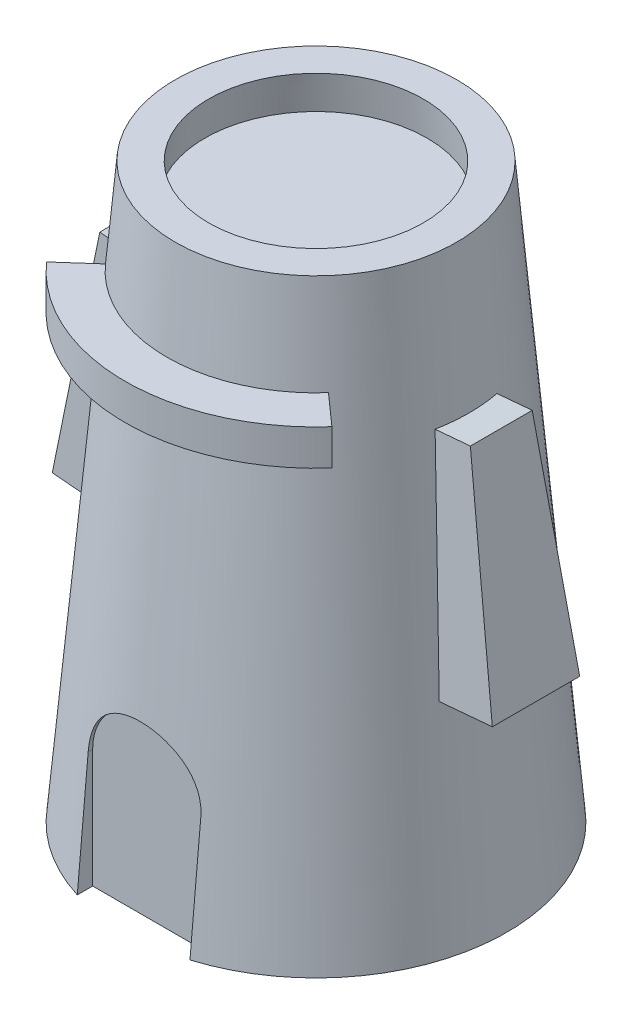
SolidWorks part; units mm, degrees
ref_plane "前视基准面" through (0, 0, 0) normal (0, 0, 1) x (1, 0, 0)
ref_plane "上视基准面" through (0, 0, 0) normal (0, 1, 0) x (1, 0, 0)
ref_plane "右视基准面" through (0, 0, 0) normal (1, 0, 0) x (0, 0, -1)
other "Configuration Table"
sketch "草图1" plane through (0, 0, 0) normal (0, 1, 0) x (1, 0, 0)
  circle A0 centre (0, 0) radius 16
extrude "凸台-拉伸1" add sketch "草图1" along normal blind 48 draft 5
sketch "草图2" plane through (0, 48, 0) normal (0, 1, 0) x (1, 0, 0)
  circle A0 centre (0, 0) radius 9
extrude "切除-拉伸1" cut sketch "草图2" against normal blind 3 draft 6 draft outward yes
ref_plane "基准面1" through (0, 0, 16) normal (0, 0, 1) x (1, 0, 0)
sketch "草图3" plane through (0, 0, 16) normal (0, 0, 1) x (1, 0, 0)
  line L0 (-4.7214, 0) -> (4.7214, 0)
  line L2 (4.7214, 0) -> (4.7214, 9.9321)
  line L4 (-4.7214, 0) -> (-4.7214, 9.9321)
  arc A0 (4.7214, 9.9321) -> (-4.7214, 9.9321) centre (0, 9.9321) ccw
  point P0 (0, 0)
extrude "切除-拉伸2" cut sketch "草图3" against normal blind 2
ref_plane "基准面2" through (0, 0, 14) normal (0, 0, 1) x (1, 0, 0)
sketch "草图5" plane through (0, 0, 14) normal (0, 0, 1) x (1, 0, 0)
  line L0 (-16.397, 0) -> (16.397, 0)
  line L1 (-16.397, 9.9321) -> (16.397, 9.9321)
  line L3 (16.397, 0) -> (16.397, 9.9321)
  line L4 (0, -55) -> (0, 55) construction
  line L5 (-16.397, 0) -> (-16.397, 9.9321)
  line L6 (4.7214, 0) -> (4.7214, 9.9321) construction
  line L7 (-4.7214, 0) -> (-4.7214, 9.9321) construction
  line L8 (4.7214, 0) -> (4.7214, 9.9321)
  line L9 (-4.7214, 0) -> (-4.7214, 9.9321)
  line L10 (4.7214, 9.9321) -> (4.7214, 0) construction
  line L11 (4.7214, 9.9321) -> (4.7214, 0)
  line L12 (-4.7214, 0) -> (-4.7214, 9.9321)
sketch "草图6" plane through (0, 0, 0) normal (0, 1, 0) x (1, 0, 0)
  circle A0 centre (0, 0) radius 12.5
  point P0 (0, 0)
ref_plane "基准面3" through (0, 40, 0) normal (0, 1, 0) x (1, 0, 0)
extrude "切除-拉伸3" cut sketch "草图6" along normal blind 43 draft 5
sketch "草图8" plane through (0, 40, 0) normal (0, 1, 0) x (1, 0, 0)
  line L1 (0, 0) -> (0, -23.7426) construction
  line L4 (-11.9615, -10.6266) -> (-9.3452, -8.3023)
  line L5 (11.9615, -10.6266) -> (9.3452, -8.3023)
  circle A0 centre (0, 0) radius 12.5005
  arc A1 (-9.3452, -8.3023) -> (9.3452, -8.3023) centre (0, 0) ccw
  arc A2 (-11.9615, -10.6266) -> (11.9615, -10.6266) centre (0, 0) ccw
  arc A3 (4.7214, -15.2875) -> (-4.7214, -15.2875) centre (0, 0) ccw construction
extrude "凸台-拉伸2" add sketch "草图8" against normal blind 3
ref_plane "基准面4" through (15.8785, 1.3892, 0) normal (0.9962, 0.0872, 0) x (0, 0, -1)
sketch "草图9" plane through (15.8785, 1.3892, 0) normal (0.9962, 0.0872, 0) x (0, 0, -1)
  line L0 (0, -1.296) -> (0, 53.4205) construction
  line L1 (-2.5924, 34.8722) -> (2.5924, 34.8722)
  line L2 (-2.5924, 34.8722) -> (-3.6621, 16.2977)
  line L3 (2.5924, 34.8722) -> (3.6621, 16.2977)
  line L4 (-3.6621, 16.2977) -> (3.6621, 16.2977)
extrude "凸台-拉伸3" add sketch "草图9" along normal blind 4 and the other way blind 1
ref_plane "基准面5" through (20.7685, 3.2894, 0) normal (0.9877, 0.1564, 0) x (0, 0, -1)
sketch "草图10" plane through (20.7685, 3.2894, 0) normal (0.9877, 0.1564, 0) x (0, 0, -1)
  line L0 (-5, 16.2977) -> (5, 16.2977) construction
sketch "草图11" plane through (20.7685, 3.2894, 0) normal (0.9877, 0.1564, 0) x (0, 0, -1)
  line L0 (2.5924, 33.487) -> (-2.5924, 33.487)
  line L2 (2.5924, 33.487) -> (-2.5924, 33.487)
  line L4 (3.6621, 14.8671) -> (2.5924, 33.487)
  line L6 (3.6621, 14.8671) -> (2.5924, 33.487)
  line L8 (-2.5924, 33.487) -> (-3.6621, 14.8671)
  line L9 (-2.5924, 33.487) -> (-3.6621, 14.8671)
  line L11 (-3.6621, 14.8671) -> (3.6621, 14.8671)
  line L12 (-3.6621, 14.8671) -> (3.6621, 14.8671)
extrude "切除-拉伸5" cut sketch "草图11" along normal blind 5
mirror "镜向1" about plane through (0, 0, 0) normal (1, 0, 0) of bodies 115
